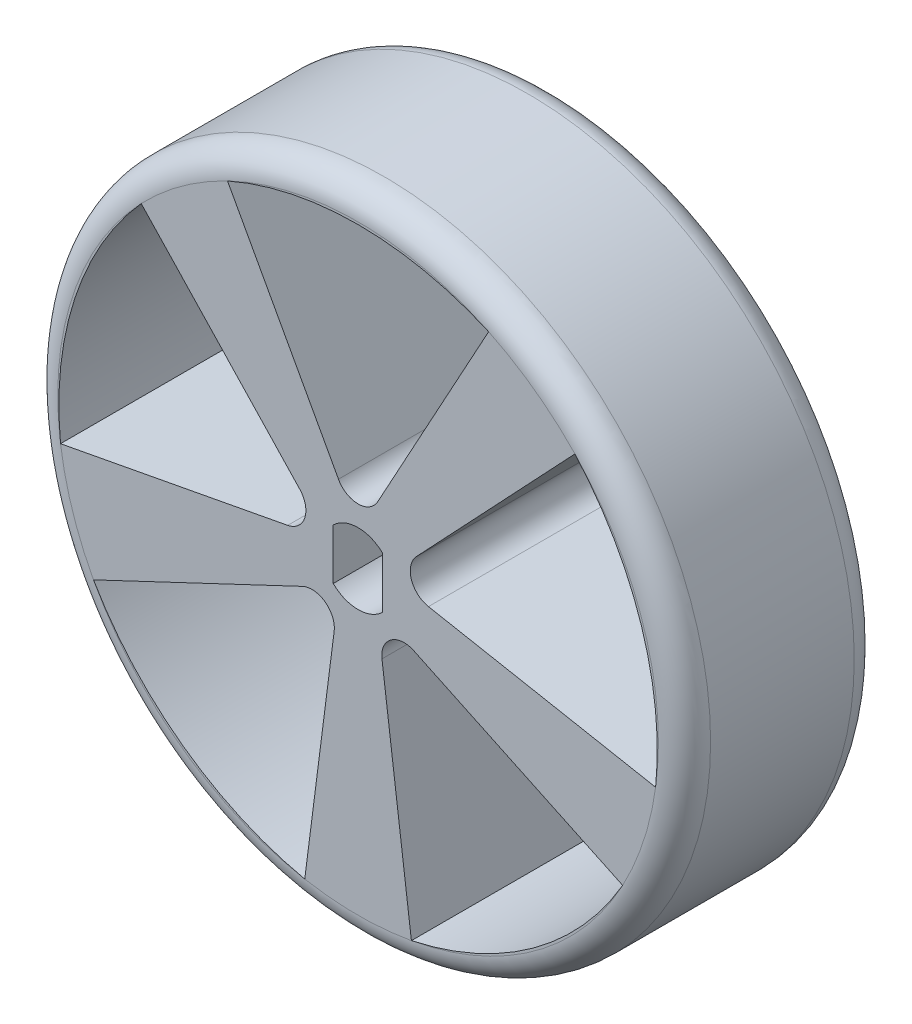
SolidWorks part; units mm, degrees
ref_plane "Front Plane" through (0, 0, 0) normal (0, 0, 1) x (1, 0, 0)
ref_plane "Top Plane" through (0, 0, 0) normal (0, 1, 0) x (1, 0, 0)
ref_plane "Right Plane" through (0, 0, 0) normal (1, 0, 0) x (0, 0, -1)
sketch "Sketch1" plane through (0, 0, 0) normal (0, 0, 1) x (1, 0, 0)
  line L0 (0, 0) -> (0, 25)
  circle A0 centre (0, 0) radius 25
  dimension "D1" = 50
extrude "Boss-Extrude1" add sketch "Sketch1" along normal blind 15 contours A0
fillet "Fillet1" radius 2 2 edges at (25, 0, 15) (25, 0, 0)
sketch "Sketch4" plane through (0, 0, 15) normal (0, 0, 1) x (1, 0, 0)
  line L0 (-1.903, 1.9412) -> (-1.903, -1.9412)
  line L1 (1.8591, 1.9833) -> (1.8591, -1.9833)
  arc A0 (1.8591, 1.9833) -> (-1.903, 1.9412) centre (0, 0) ccw
  arc A1 (-1.903, -1.9412) -> (1.8591, -1.9833) centre (0, 0) ccw
extrude "Cut-Extrude1" cut sketch "Sketch4" against normal blind 4
sketch "Sketch7" plane through (0, 0, 15) normal (0, 0, 1) x (1, 0, 0)
  circle A0 centre (0, 0) radius 1.04
extrude "Cut-Extrude2" cut sketch "Sketch7" against normal through all
sketch "Sketch8" plane through (0, 0, 0) normal (0, 0, -1) x (-1, 0, 0)
  line L2 (-1.5, 5.1792) -> (-10, 20.7123)
  line L3 (1.5, 5.1792) -> (10, 20.7123)
  circle A3 centre (0, 0) radius 23 construction
  arc A4 (10, 20.7123) -> (-10, 20.7123) centre (0, -1.9385) ccw
  arc A5 (-1.5, 5.1792) -> (1.5, 5.1792) centre (0, 6) ccw
  point P8 (0, 0)
  dimension "D2" = 20
  dimension "D3" = 6
  dimension "D4" = 24.76
  dimension "D1" = 3
extrude "Cut-Extrude3" cut sketch "Sketch8" against normal up to next contours L2 A4 L3 A5
pattern_circular "CirPattern1" count 5 over 360 about axis through (0, 0, 0) along (0, 0, 1) of "Cut-Extrude3"
